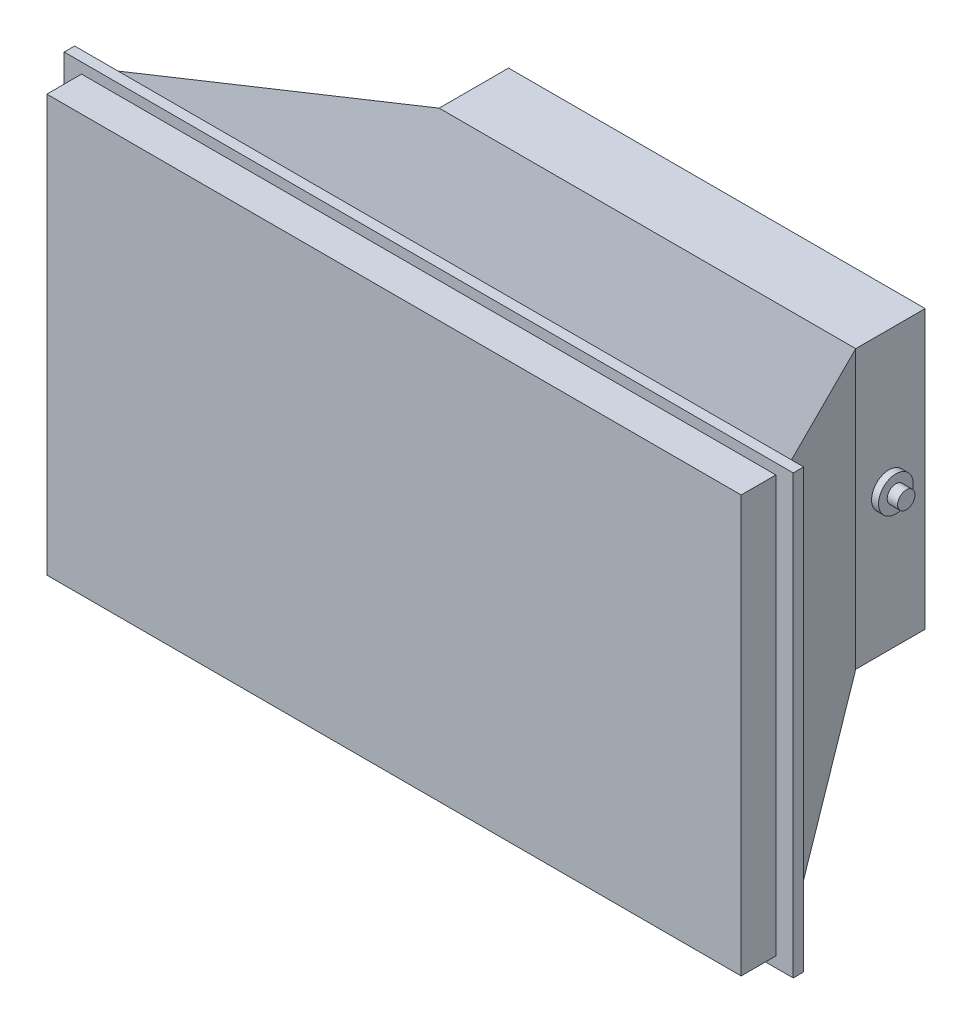
SolidWorks part; units mm, degrees
ref_plane "前视基准面" through (0, 0, 0) normal (0, 0, 1) x (1, 0, 0)
ref_plane "上视基准面" through (0, 0, 0) normal (0, 1, 0) x (1, 0, 0)
ref_plane "右视基准面" through (0, 0, 0) normal (1, 0, 0) x (0, 0, -1)
sketch "草图2" plane through (0, 0, 0) normal (0, 0, 1) x (1, 0, 0)
  line L0 (-143.0704, 0) -> (151.7589, 0) construction
  line L2 (0, 89.057) -> (0, -123.2317) construction
  line L5 (-100, 60) -> (100, 60)
  line L6 (-100, 60) -> (-100, -60)
  line L7 (-100, -60) -> (100, -60)
  line L8 (100, 60) -> (100, -60)
  dimension "D1" = 200
  dimension "D2" = 120
extrude "凸台-拉伸1" add sketch "草图2" against normal blind 10 contours L5 L8 L7 L6
sketch "草图3" plane through (0, 0, -10) normal (0, 0, -1) x (-1, 0, 0)
  line L0 (100, 60) -> (-100, 60) construction
  line L1 (-105, 63) -> (105, 63)
  line L2 (-105, 63) -> (-105, -63)
  line L3 (-105, -63) -> (105, -63)
  line L4 (105, 63) -> (105, -63)
  line L5 (-100, 60) -> (-100, -60) construction
  line L6 (100, 60) -> (100, -60) construction
  line L7 (100, -60) -> (-100, -60) construction
  dimension "D1" = 3
  dimension "D2" = 5
  dimension "D3" = 5
  dimension "D4" = 3
extrude "凸台-拉伸2" add sketch "草图3" along normal blind 3
ref_plane "基准面1" through (0, 0, -73) normal (0, 0, -1) x (-1, 0, 0)
sketch "草图4" plane through (0, 0, -73) normal (0, 0, -1) x (-1, 0, 0)
  line L0 (0, 53.3042) -> (0, -59.1618) construction
  line L2 (-90.4201, 0) -> (82.326, 0) construction
  line L3 (-60, 40) -> (60, 40)
  line L4 (-60, 40) -> (-60, -40)
  line L5 (-60, -40) -> (60, -40)
  line L6 (60, 40) -> (60, -40)
  dimension "D1" = 80
  dimension "D2" = 120
sketch "草图5" plane through (0, 0, -13) normal (0, 0, -1) x (-1, 0, 0)
  line L0 (105, 63) -> (-105, 63) construction
  line L1 (-100, 60) -> (100, 60)
  line L2 (-100, 60) -> (-100, -60)
  line L3 (-100, -60) -> (100, -60)
  line L4 (100, 60) -> (100, -60)
  line L5 (-105, 63) -> (-105, -63) construction
  dimension "D1" = 200
  dimension "D2" = 120
  dimension "D3" = 3
  dimension "D4" = 5
loft "放样2" add profiles "草图5", "草图4"
sketch "草图8" plane through (0, 0, -73) normal (0, 0, -1) x (-1, 0, 0)
  line L1 (-60, 40) -> (60, 40)
  line L2 (-60, 40) -> (-60, -40)
  line L3 (-60, -40) -> (60, -40)
  line L4 (60, 40) -> (60, -40)
extrude "凸台-拉伸4" add sketch "草图8" along normal blind 20
sketch "草图9" plane through (60, 0, 0) normal (1, 0, 0) x (0, 0, -1)
  circle A0 centre (82.568, 0) radius 5
extrude "凸台-拉伸5" add sketch "草图9" along normal blind 2
sketch "草图10" plane through (62, 0, 0) normal (1, 0, 0) x (0, 0, -1)
  circle A0 centre (82.568, 0) radius 2.5
extrude "凸台-拉伸6" add sketch "草图10" along normal blind 3
mirror "镜向1" about plane through (0, 0, 0) normal (1, 0, 0) of "凸台-拉伸5", "凸台-拉伸6"
